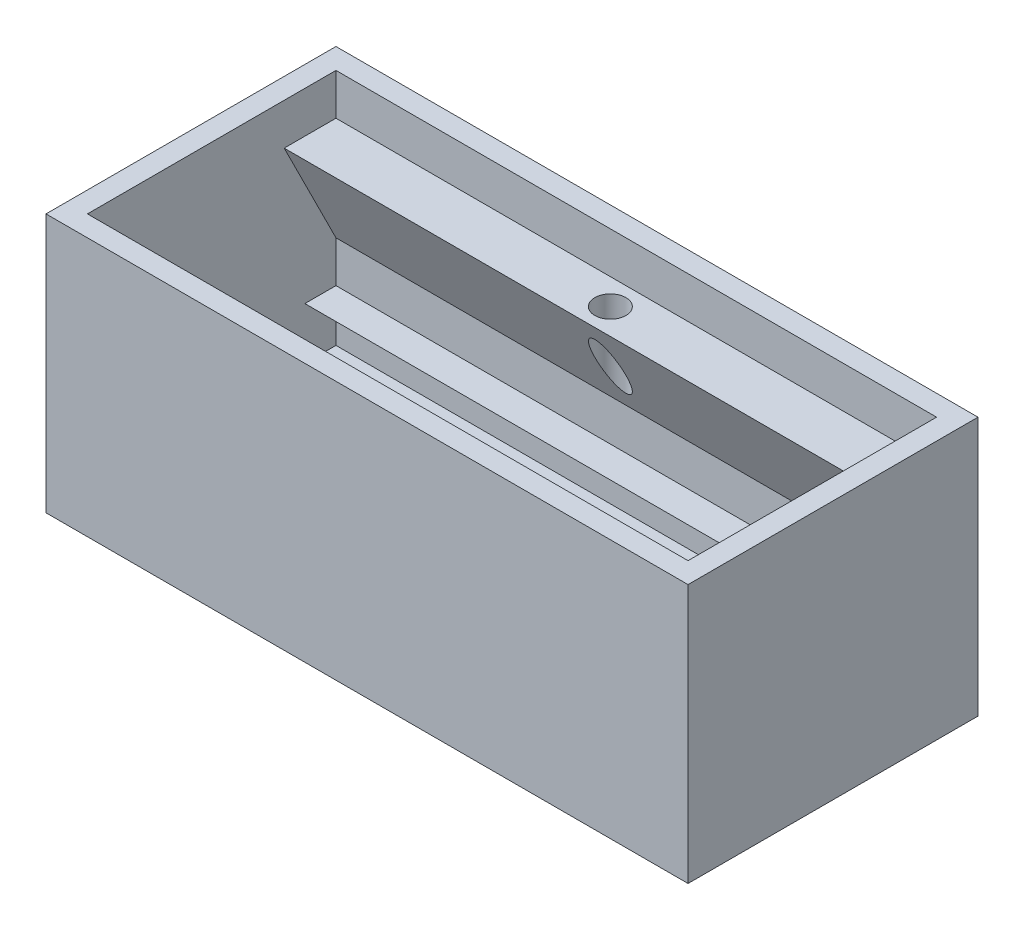
SolidWorks part; units mm, degrees
ref_plane "Front" through (0, 0, 0) normal (0, 0, 1) x (1, 0, 0)
ref_plane "Top" through (0, 0, 0) normal (0, 1, 0) x (1, 0, 0)
ref_plane "Right" through (0, 0, 0) normal (1, 0, 0) x (0, 0, -1)
sketch "Sketch1" plane through (0, 0, 0) normal (0, 1, 0) x (1, 0, 0)
  line L1 (0, 0) -> (62, 0)
  line L2 (0, 0) -> (0, 28)
  line L3 (0, 28) -> (62, 28)
  line L4 (62, 0) -> (62, 28)
  dimension "D1" = 62
  dimension "D2" = 28
extrude "Boss-Extrude1" add sketch "Sketch1" along normal blind 25
sketch "Sketch2" plane through (0, 25, 0) normal (0, 1, 0) x (1, 0, 0)
  line L0 (0, 28) -> (0, 0) construction
  line L1 (2, 26) -> (60, 26)
  line L2 (2, 26) -> (2, 2)
  line L3 (2, 2) -> (60, 2)
  line L4 (60, 26) -> (60, 2)
  line L5 (62, 28) -> (0, 28) construction
  line L6 (62, 0) -> (62, 28) construction
  line L7 (0, 0) -> (62, 0) construction
  dimension "D1" = 2
  dimension "D2" = 2
  dimension "D3" = 2
  dimension "D4" = 2
extrude "Cut-Extrude1" cut sketch "Sketch2" against normal blind 23
sketch "Sketch3" plane through (2, 0, 0) normal (1, 0, 0) x (0, 0, -1)
  line L0 (26, 11) -> (21, 21)
  line L1 (26, 2) -> (26, 25) construction
  line L2 (21, 21) -> (26, 21)
  line L3 (26, 21) -> (26, 11)
  line L4 (0, 25) -> (28, 25) construction
  dimension "D1" = 5
  dimension "D2" = 10
  dimension "D3" = 4
extrude "Boss-Extrude3" add sketch "Sketch3" along normal up to surface (58 mm away) up to face at (60, 13.5, -14)
hole_wizard "Ø1.5 (1.5) Diameter Hole1" positions "Sketch5" profile "Sketch4" hole size "Ø1.5" standard "ANSI Metric" end condition up to next
sketch "Sketch5" plane through (0, 0, 0) normal (0, -1, 0) x (-1, 0, 0)
  line L0 (0, 0) -> (-62, 0) construction
  line L1 (0, 28) -> (0, 0) construction
  point P0 (-7.5, 7.5)
  point P2 (-5.5, 7.5)
  point P4 (-3.5, 7.5)
  dimension "D1" = 7.5
  dimension "D2" = 3.5
  dimension "D3" = 2
  dimension "D4" = 2
sketch "Sketch4" plane through (7.5, 0, -7.5) normal (1, 0, 0) x (0, 0, -1)
  line L0 (0, 0) -> (0, 2)
  line L1 (0, 2) -> (0.75, 2)
  line L2 (0.75, 2) -> (0.75, 0)
  line L5 (0.75, 0) -> (0, 0)
  line L11 (0, -6.35) -> (0, 107.95) construction
  dimension "Thru Hole Dia." = 1.5
  dimension "Thru Hole Depth" = 2
hole_wizard "Ø2.0 (2) Diameter Hole1" positions "Sketch7" profile "Sketch6" hole size "Ø2.0" standard "ANSI Metric"
sketch "Sketch7" plane through (0, 0, 0) normal (0, -1, 0) x (-1, 0, 0)
  line L0 (-62, 0) -> (-62, 28) construction
  line L1 (0, 0) -> (-62, 0) construction
  point P0 (-53, 21)
  dimension "D1" = 9
  dimension "D2" = 21
sketch "Sketch6" plane through (53, 0, -21) normal (1, 0, 0) x (0, 0, -1)
  line L0 (0, 0) -> (0, 2)
  line L1 (0, 2) -> (1, 2)
  line L2 (1, 2) -> (1, 0)
  line L5 (1, 0) -> (0, 0)
  line L11 (0, -6.35) -> (0, 107.95) construction
  dimension "Thru Hole Dia." = 2
  dimension "Thru Hole Depth" = 2
hole_wizard "Ø3.5 (3.5) Diameter Hole1" positions "Sketch9" profile "Sketch8" hole size "Ø3.5" standard "ANSI Metric"
sketch "Sketch9" plane through (0, 0, 0) normal (0, -1, 0) x (-1, 0, 0)
  line L0 (0, 0) -> (-62, 0) construction
  line L1 (-62, 0) -> (-62, 28) construction
  point P0 (-40, 22)
  dimension "D1" = 22
  dimension "D2" = 22
sketch "Sketch8" plane through (40, 0, -22) normal (1, 0, 0) x (0, 0, -1)
  line L0 (0, 0) -> (0, 2)
  line L1 (0, 2) -> (1.75, 2)
  line L2 (1.75, 2) -> (1.75, 0)
  line L5 (1.75, 0) -> (0, 0)
  line L11 (0, -6.35) -> (0, 107.95) construction
  dimension "Thru Hole Dia." = 3.5
  dimension "Thru Hole Depth" = 2
sketch "Sketch10" plane through (2, 0, 0) normal (1, 0, 0) x (0, 0, -1)
  line L0 (26, 4) -> (23, 7)
  line L1 (26, 2) -> (26, 11) construction
  line L2 (23, 7) -> (26, 7)
  line L3 (26, 7) -> (26, 4)
  dimension "D1" = 2
  dimension "D2" = 3
  dimension "D3" = 3
extrude "Boss-Extrude4" add sketch "Sketch10" along normal up to next
hole_wizard "Ø3.0 (3) Diameter Hole1" positions "Sketch12" profile "Sketch11" hole size "Ø3.0" standard "ANSI Metric"
sketch "Sketch12" plane through (0, 21, 0) normal (0, 1, 0) x (1, 0, 0)
  line L0 (60, 26) -> (2, 26) construction
  line L1 (2, 26) -> (2, 21) construction
  point P0 (31, 23.5)
  dimension "D1" = 2.5
  dimension "D2" = 29
sketch "Sketch11" plane through (31, 21, -23.5) normal (1, 0, 0) x (0, 0, 1)
  line L0 (0, 0) -> (0, 5)
  line L1 (0, 5) -> (1.5, 5)
  line L2 (1.5, 5) -> (1.5, 0)
  line L5 (1.5, 0) -> (0, 0)
  line L11 (0, -6.35) -> (0, 107.95) construction
  dimension "Thru Hole Dia." = 3
  dimension "Thru Hole Depth" = 5
